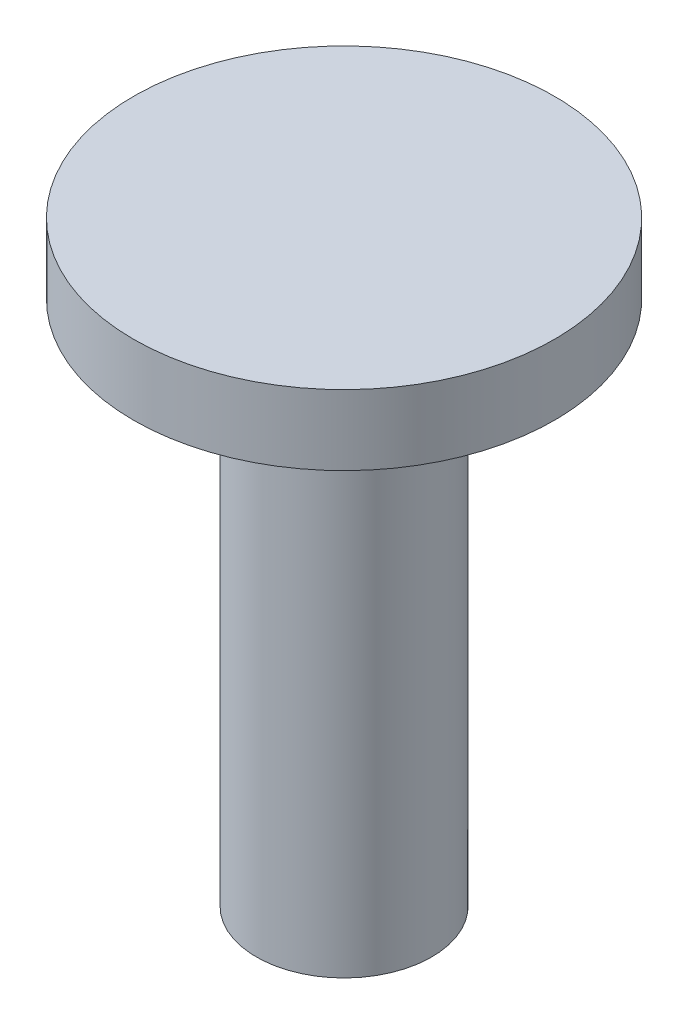
SolidWorks part; units mm, degrees
material "AISI 304"
ref_plane "前视基准面" through (0, 0, 0) normal (0, 0, 1) x (1, 0, 0)
ref_plane "上视基准面" through (0, 0, 0) normal (0, 1, 0) x (1, 0, 0)
ref_plane "右视基准面" through (0, 0, 0) normal (1, 0, 0) x (0, 0, -1)
other "Configuration Table"
sketch "草图1" plane through (0, 0, 0) normal (0, 1, 0) x (1, 0, 0)
  circle A0 centre (0, 0) radius 2.4
  dimension "D1" = 4.8
extrude "凸台-拉伸1" add sketch "草图1" along normal blind 0.8
sketch "草图2" plane through (0, 0, 0) normal (0, -1, 0) x (1, 0, 0)
  circle A0 centre (0, 0) radius 1
  dimension "D1" = 2
extrude "凸台-拉伸2" add sketch "草图2" along normal blind 6
